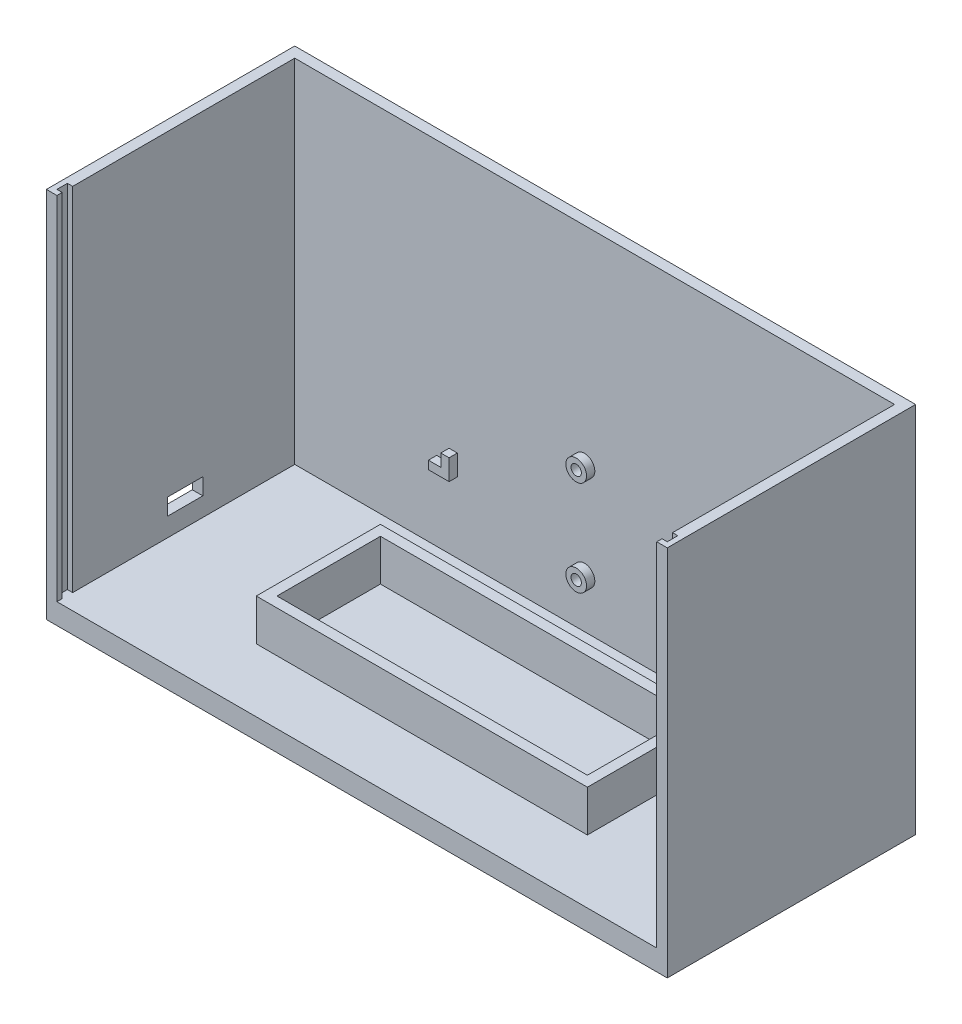
SolidWorks part; units mm, degrees
ref_plane "Front Plane" through (0, 0, 0) normal (0, 0, 1) x (1, 0, 0)
ref_plane "Top Plane" through (0, 0, 0) normal (0, 1, 0) x (1, 0, 0)
ref_plane "Right Plane" through (0, 0, 0) normal (1, 0, 0) x (0, 0, -1)
sketch "Sketch1" plane through (0, 0, 0) normal (0, 1, 0) x (1, 0, 0)
  line L1 (-75, -30) -> (75, -30)
  line L2 (-75, -30) -> (-75, 30)
  line L3 (-75, 30) -> (75, 30)
  line L4 (75, -30) -> (75, 30)
  line L5 (-75, -30) -> (75, 30) construction
  line L6 (-75, 30) -> (75, -30) construction
  point P0 (0, 0)
  dimension "D1" = 60
  dimension "D2" = 150
extrude "Boss-Extrude1" add sketch "Sketch1" along normal blind 90
sketch "Sketch2" plane through (0, 90, 0) normal (0, 1, 0) x (1, 0, 0)
  line L0 (75, 30) -> (-75, 30) construction
  line L1 (-75, 30) -> (-75, -30) construction
  line L2 (75, -30) -> (75, 30) construction
  line L18 (72.46, -32.54) -> (72.46, 27.46)
  line L19 (-72.46, -32.54) -> (72.46, -32.54)
  line L20 (72.46, 27.46) -> (-72.46, 27.46)
  line L21 (-72.46, 27.46) -> (-72.46, -32.54)
  dimension "D2" = 2.54
  dimension "D1" = 60
  dimension "D3" = 2.54
  dimension "D4" = 2.54
extrude "Cut-Extrude1" cut sketch "Sketch2" against normal blind 85
sketch "Sketch6" plane through (0, 0, -27.46) normal (0, 0, 1) x (1, 0, 0)
  line L0 (-72.46, 5) -> (-72.46, 90) construction
  circle A0 centre (-2.46, 39.8292) radius 2.5
  circle A4 centre (55.54, 39.8292) radius 2.5
  circle A5 centre (55.54, 16.8292) radius 2.5
  circle A6 centre (-2.46, 16.8292) radius 2.5
  circle A7 centre (-2.46, 39.8292) radius 1.25
  circle A8 centre (55.54, 39.8292) radius 1.25
  circle A9 centre (55.54, 16.8292) radius 1.25
  circle A10 centre (-2.46, 16.8292) radius 1.25
  point P7 (26.54, 39.8292)
  point P18 (-72.46, 47.5)
  dimension "D1" = 5
  dimension "D7" = 2.5
  dimension "D8" = 70
  dimension "D2" = 2
  dimension "D3" = 58
  dimension "D4" = 29
  dimension "D6" = 23
  dimension "D5" = 2
extrude "Boss-Extrude2" add sketch "Sketch6" along normal blind 2
sketch "Sketch7" plane through (0, 0, -27.46) normal (0, 0, 1) x (1, 0, 0)
  line L0 (-38.17, 24.0301) -> (-38.17, 22.0301)
  line L1 (-38.17, 22.0301) -> (-33.17, 22.0301)
  line L2 (-33.17, 22.0301) -> (-33.17, 27.0301)
  line L3 (-33.17, 27.0301) -> (-35.17, 27.0301)
  line L4 (-35.17, 27.0301) -> (-35.17, 24.0301)
  line L5 (-35.17, 24.0301) -> (-38.17, 24.0301)
  line L6 (-72.46, 5) -> (-72.46, 90) construction
  point P6 (-38.17, 23.0301)
  dimension "D1" = 2
  dimension "D2" = 2
  dimension "D3" = 5
  dimension "D4" = 5
  dimension "D5" = 34.29
extrude "Boss-Extrude3" add sketch "Sketch7" along normal blind 2
sketch "Sketch8" plane through (-75, 0, 0) normal (-1, 0, 0) x (0, 0, 1)
  line L0 (-30, 90) -> (-30, 0) construction
  line L1 (-5.25, 9.5248) -> (3.25, 9.5248)
  line L2 (-5.25, 9.5248) -> (-5.25, 13.5248)
  line L3 (-5.25, 13.5248) -> (3.25, 13.5248)
  line L4 (3.25, 9.5248) -> (3.25, 13.5248)
  dimension "D1" = 8.5
  dimension "D2" = 4
  dimension "D3" = 24.75
extrude "Cut-Extrude4" cut sketch "Sketch8" against normal blind 2.54
sketch "Sketch12" plane through (0, 5, 0) normal (0, 1, 0) x (1, 0, 0)
  line L1 (-39.57, 15.2736) -> (40.43, 15.2736)
  line L2 (-39.57, 15.2736) -> (-39.57, -14.7264)
  line L3 (-39.57, -14.7264) -> (40.43, -14.7264)
  line L4 (40.43, 15.2736) -> (40.43, -14.7264)
  dimension "D1" = 30
  dimension "D2" = 80
extrude "Boss-Extrude5" add sketch "Sketch12" along normal blind 10 contours L2 L1 L4 L3
sketch "Sketch13" plane through (0, 15, 0) normal (0, 1, 0) x (1, 0, 0)
  line L0 (-39.57, 15.2736) -> (-39.57, -14.7264) construction
  line L1 (-37.07, 12.7736) -> (37.93, 12.7736)
  line L2 (-37.07, 12.7736) -> (-37.07, -12.2264)
  line L3 (-37.07, -12.2264) -> (37.93, -12.2264)
  line L4 (37.93, 12.7736) -> (37.93, -12.2264)
  line L5 (-39.57, -14.7264) -> (40.43, -14.7264) construction
  dimension "D1" = 75
  dimension "D2" = 25
  dimension "D3" = 2.5
  dimension "D4" = 2.5
extrude "Cut-Extrude6" cut sketch "Sketch13" against normal blind 10
sketch "Sketch16" plane through (0, 90, 0) normal (0, 1, 0) x (1, 0, 0)
  line L0 (-72.46, 27.46) -> (-72.46, -30) construction
  line L1 (-72.46, -28.73) -> (-73.73, -28.73)
  line L2 (-72.46, -28.73) -> (-72.46, -26.19)
  line L3 (-72.46, -26.19) -> (-73.73, -26.19)
  line L4 (-73.73, -28.73) -> (-73.73, -26.19)
  line L5 (-75, -30) -> (-72.46, -30) construction
  line L6 (-75, 30) -> (-75, -30) construction
  line L12 (72.46, -26.19) -> (73.73, -26.19)
  line L13 (73.73, -28.73) -> (73.73, -26.19)
  line L14 (72.46, -28.73) -> (73.73, -28.73)
  line L15 (72.46, -28.73) -> (72.46, -26.19)
  point P10 (0, -27.46)
  dimension "D1" = 1.27
  dimension "D2" = 2.54
  dimension "D3" = 1.27
extrude "Cut-Extrude7" cut sketch "Sketch16" against normal blind 85
